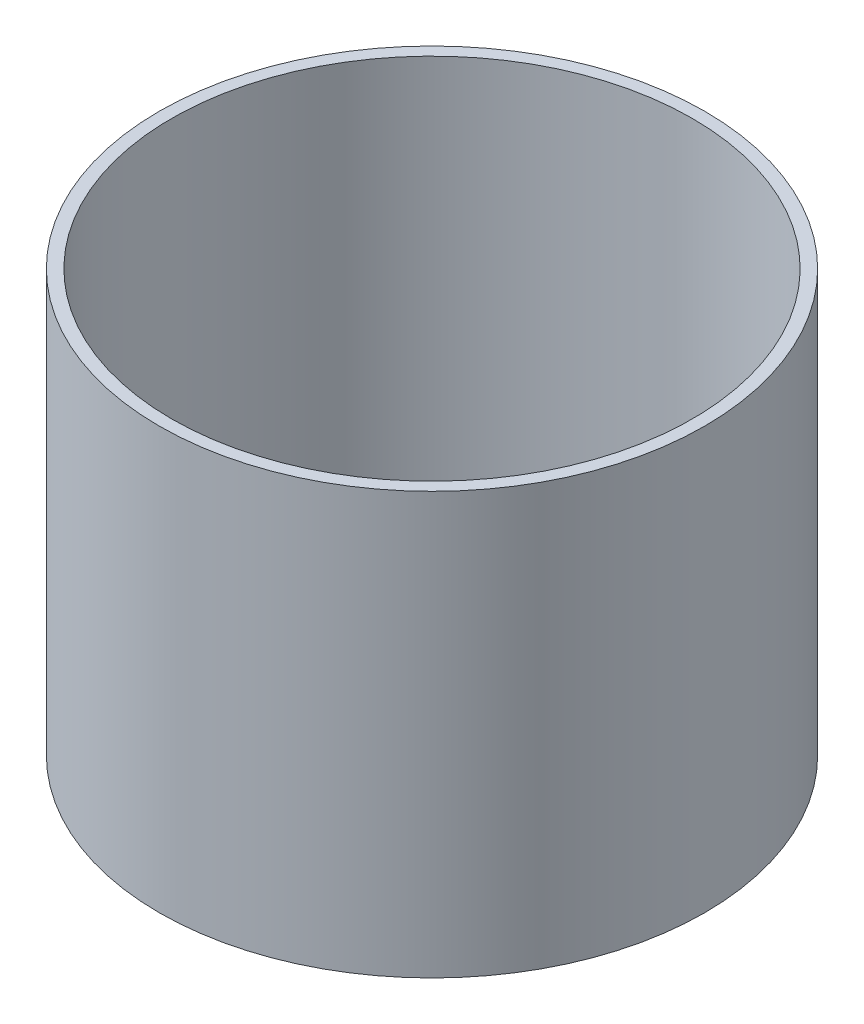
SolidWorks part; units mm, degrees
ref_plane "Front Plane" through (0, 0, 0) normal (0, 0, 1) x (1, 0, 0)
ref_plane "Top Plane" through (0, 0, 0) normal (0, 1, 0) x (1, 0, 0)
ref_plane "Right Plane" through (0, 0, 0) normal (1, 0, 0) x (0, 0, -1)
sketch "Sketch1" plane through (0, 0, 0) normal (0, 1, 0) x (1, 0, 0)
  circle A0 centre (0, 0) radius 10.5
  circle A1 centre (0, 0) radius 11
  dimension "D2" = 22
  dimension "D1" = 0.5
extrude "Boss-Extrude1" add sketch "Sketch1" along normal blind 17
equation "\"D\"= 22"
equation "\"D2@Sketch1\"=\"D\""
